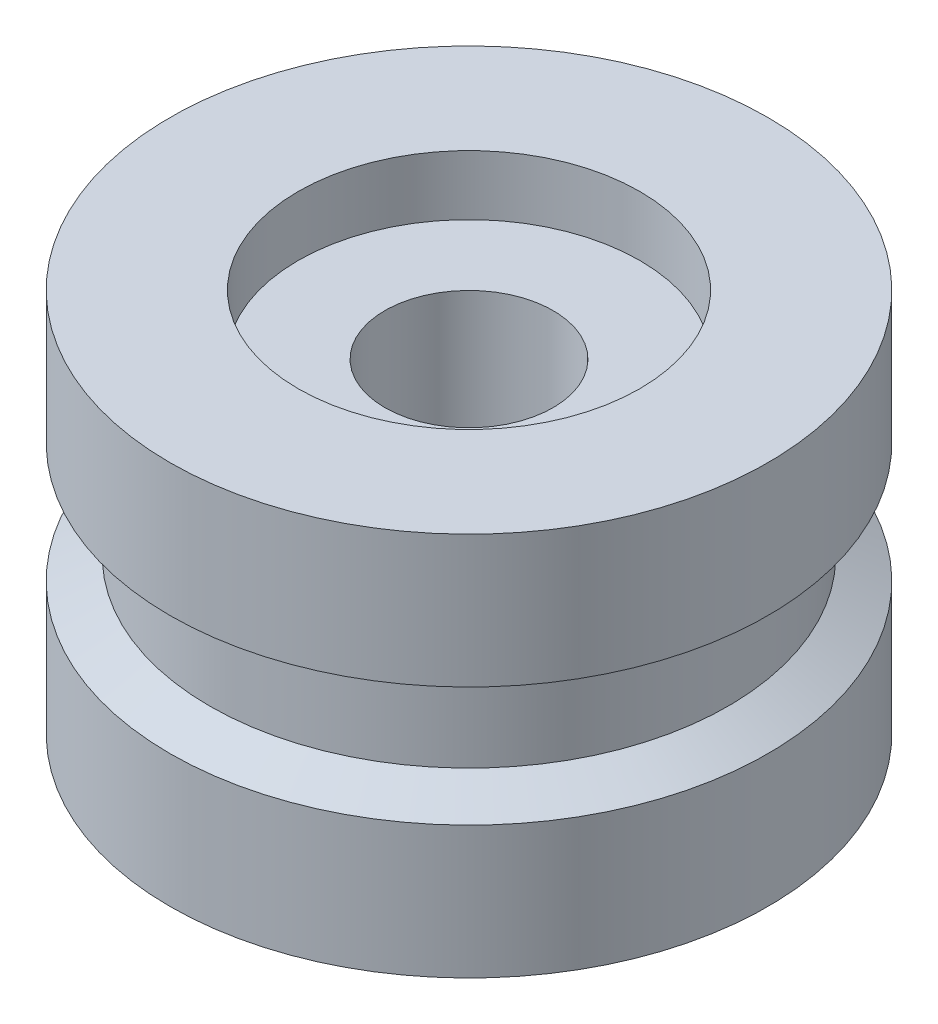
SolidWorks part; units mm, degrees
material "3.1655 (EN AW-2011)"
ref_plane "Alzado" through (0, 0, 0) normal (0, 0, 1) x (1, 0, 0)
ref_plane "Planta" through (0, 0, 0) normal (0, 1, 0) x (1, 0, 0)
ref_plane "Vista lateral" through (0, 0, 0) normal (1, 0, 0) x (0, 0, -1)
sketch "Croquis1" plane through (0, 0, 0) normal (0, 1, 0) x (1, 0, 0)
  circle A0 centre (0, 0) radius 35
  circle A1 centre (0, 0) radius 9.85
  dimension "D1" = 70
  dimension "D2" = 19.7
extrude "Saliente-Extruir1" add sketch "Croquis1" along normal mid plane 31
sketch "Croquis2" plane through (0, 0, 0) normal (1, 0, 0) x (0, 0, -1)
  line L0 (-30.36, 0) -> (-35, 0) construction
  line L1 (-35, 15.5) -> (-35, -15.5) construction
  line L2 (-35, 0) -> (-35, 7) construction
  line L3 (-20, -15.5) -> (-20, -22.5)
  line L4 (-35, 15.5) -> (-20, 15.5)
  line L5 (-35, 15.5) -> (-35, 22.5)
  line L6 (-35, 22.5) -> (-20, 22.5)
  line L7 (-20, 15.5) -> (-20, 22.5)
  line L8 (-35, -22.5) -> (-20, -22.5)
  line L9 (-35, -15.5) -> (-35, -22.5)
  line L10 (-35, -15.5) -> (-20, -15.5)
  line L12 (-30.36, -4.5) -> (-35, -7)
  line L14 (-35, -7) -> (-35, 7)
  line L15 (-35, 7) -> (-30.36, 4.5)
  line L17 (-30.36, -15.5) -> (-35, -15.5)
  line L19 (-30.36, 15.5) -> (-35, 15.5)
  line L21 (-30.36, -4.5) -> (-30.36, 4.5)
  point P20 (-35, 0)
  dimension "D2" = 7
  dimension "D3" = 9
  dimension "D4" = 14
ref_axis "Eje1" through (0, 15.5, 0) along (0, -1, 0)
revolve "Cortar-Revolución1" cut sketch "Croquis2" angle 360 about axis through (0, 15.5, 0) along (0, -1, 0)
sketch "Croquis3" plane through (0, 0, 0) normal (1, 0, 0) x (0, 0, -1)
  line L1 (-35, 15.5) -> (-20, 15.5)
  line L2 (-35, 15.5) -> (-35, 22.5)
  line L3 (-35, 22.5) -> (-20, 22.5)
  line L4 (-20, 15.5) -> (-20, 22.5)
  line L5 (-35, -15.5) -> (-20, -15.5)
  line L6 (-35, -15.5) -> (-35, -22.5)
  line L7 (-35, -22.5) -> (-20, -22.5)
  line L8 (-20, -15.5) -> (-20, -22.5)
  dimension "D1" = 15
  dimension "D2" = 15
  dimension "D3" = 7
  dimension "D4" = 7
revolve "Revolución1" add sketch "Croquis3" angle 360 about axis through (0, 15.5, 0) along (0, -1, 0)
